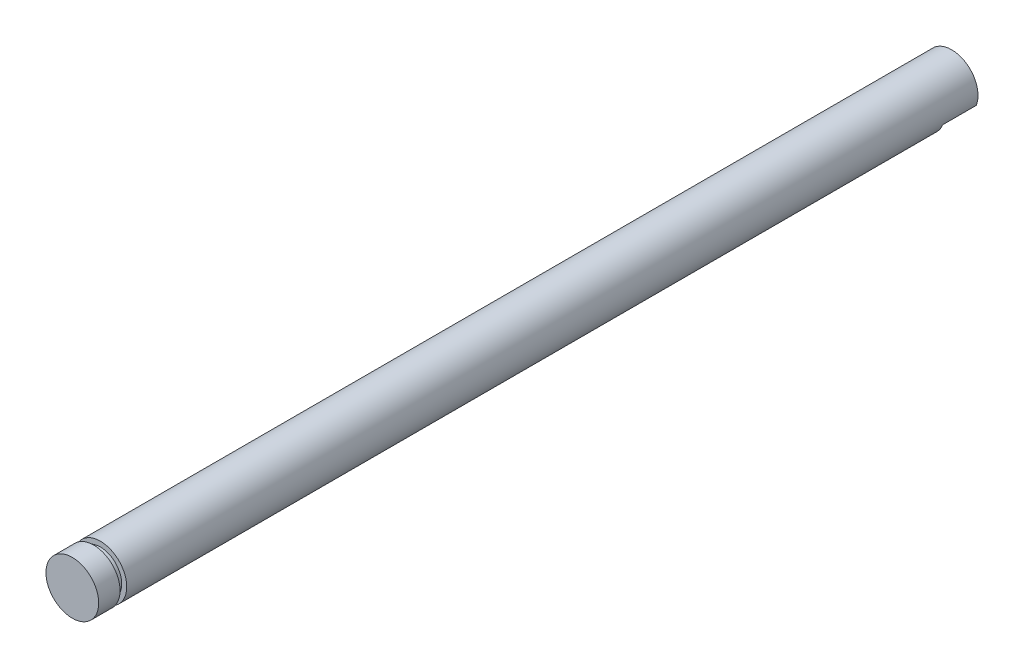
SolidWorks part; units mm, degrees
material "6061 Alloy"
ref_plane "Front Plane" through (0, 0, 0) normal (0, 0, 1) x (1, 0, 0)
ref_plane "Top Plane" through (0, 0, 0) normal (0, 1, 0) x (1, 0, 0)
ref_plane "Right Plane" through (0, 0, 0) normal (1, 0, 0) x (0, 0, -1)
sketch "Sketch1" plane through (0, 0, 0) normal (0, 0, 1) x (1, 0, 0)
  circle A0 centre (0, 0) radius 2
  dimension "D1" = 4
extrude "Boss-Extrude1" add sketch "Sketch1" along normal mid plane 66.675
sketch "Sketch2" plane through (0, 0, 0) normal (1, 0, 0) x (0, 0, -1)
  line L0 (33.3375, 2) -> (-33.3375, 2) construction
  line L1 (-31.2103, 2) -> (-31.7182, 2)
  line L2 (-31.2103, 2) -> (-31.2102, 1.619)
  line L3 (-31.2102, 1.619) -> (-31.7182, 1.619)
  line L4 (-31.7182, 2) -> (-31.7182, 1.619)
  line L6 (-30.1625, 7.5341) -> (-30.1625, 0) construction
  dimension "D1" = 1.0477
  dimension "D2" = 0.508
  dimension "D3" = 0.381
ref_axis "Axis1" through (0, 0, 33.3375) along (0, 0, -1)
revolve "Cut-Revolve1" cut sketch "Sketch2" angle 360 about axis through (0, 0, 33.3375) along (0, 0, -1)
sketch "Sketch3" plane through (0, 0, 0) normal (1, 0, 0) x (0, 0, -1)
  line L0 (33.3375, 3) -> (33.3375, -3) construction
  line L1 (33.3375, -0.73) -> (30.7975, -0.73)
  line L2 (33.3375, -0.73) -> (33.3375, -2)
  line L3 (33.3375, -2) -> (30.7975, -2)
  line L4 (30.7975, -0.73) -> (30.7975, -2)
  line L5 (-31.2103, -2) -> (33.3375, -2) construction
  dimension "D1" = 2.54
  dimension "D2" = 1.27
extrude "Cut-Extrude1" cut sketch "Sketch3" against normal through all both and the other way through all
